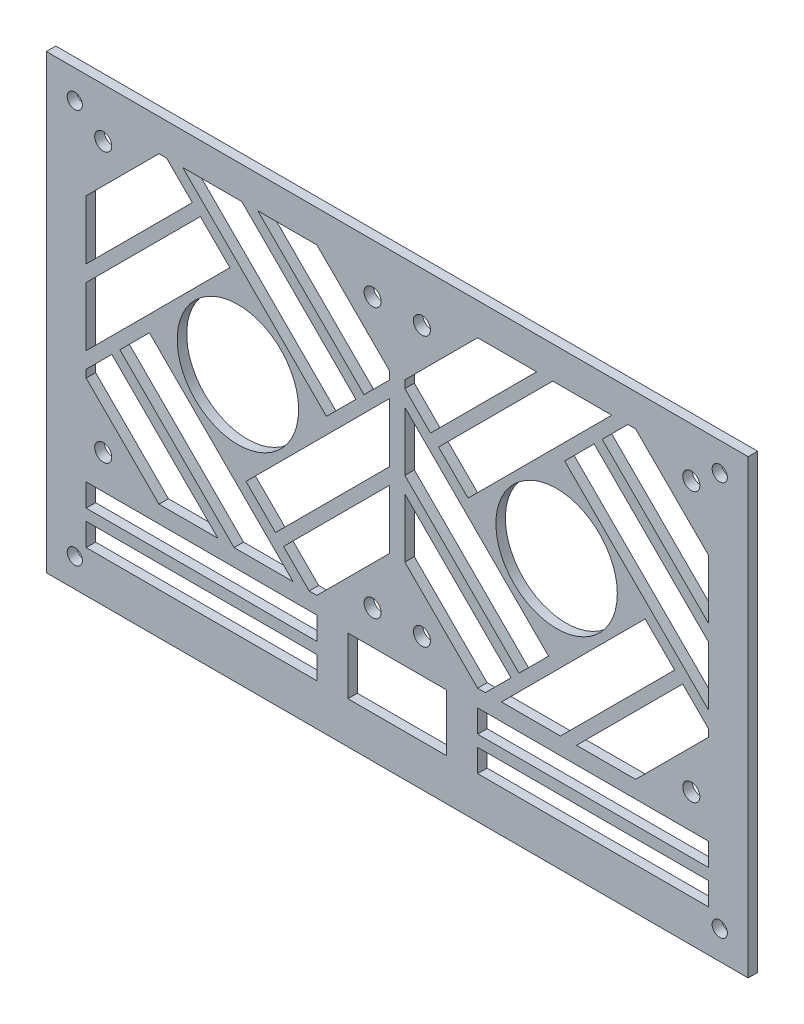
SolidWorks part; units mm, degrees
ref_plane "Front Plane" through (0, 0, 0) normal (0, 0, 1) x (1, 0, 0)
ref_plane "Top Plane" through (0, 0, 0) normal (0, 1, 0) x (1, 0, 0)
ref_plane "Right Plane" through (0, 0, 0) normal (1, 0, 0) x (0, 0, -1)
sketch "Sketch1" plane through (0, 0, 0) normal (0, 0, 1) x (1, 0, 0)
  line L1 (-92.5, -65.5) -> (92.5, -65.5)
  line L2 (-92.5, -65.5) -> (-92.5, 49.5)
  line L3 (-92.5, 49.5) -> (92.5, 49.5)
  line L4 (92.5, -65.5) -> (92.5, 49.5)
  point P0 (0, 0)
  dimension "D1" = 65.5
  dimension "D2" = 49.5
  dimension "D3" = 185
extrude "Boss-Extrude1" add sketch "Sketch1" along normal blind 2.5
sketch "Sketch2" plane through (0, 0, 2.5) normal (0, 0, 1) x (1, 0, 0)
  line L0 (-92.5, 49.5) -> (-92.5, -65.5) construction
  line L1 (92.5, -65.5) -> (92.5, 49.5) construction
  line L2 (-92.5, -65.5) -> (92.5, -65.5) construction
  circle A0 centre (-42, 5) radius 16
  circle A1 centre (42, 5) radius 16
  dimension "D1" = 50.5
  dimension "D2" = 32
  dimension "D3" = 32
  dimension "D4" = 50.5
  dimension "D5" = 70.5
  dimension "D6" = 70.5
extrude "Cut-Extrude1" cut sketch "Sketch2" against normal through all
sketch "Sketch5" plane through (0, 0, 2.5) normal (0, 0, 1) x (1, 0, 0)
  line L0 (-92.5, -65.5) -> (92.5, -65.5) construction
  line L1 (-13, -54.5) -> (13, -54.5)
  line L2 (-13, -54.5) -> (-13, -39.5)
  line L3 (-13, -39.5) -> (13, -39.5)
  line L4 (13, -54.5) -> (13, -39.5)
  line L5 (-13, -54.5) -> (13, -39.5) construction
  line L6 (-13, -39.5) -> (13, -54.5) construction
  point P0 (0, -47)
  dimension "D1" = 26
  dimension "D2" = 15
  dimension "D3" = 11
extrude "Cut-Extrude4" cut sketch "Sketch5" against normal blind 10
sketch "Sketch8" plane through (0, 0, 2.5) normal (0, 0, 1) x (1, 0, 0)
  line L0 (-82, 10.2548) -> (-54.0208, 38.234)
  line L1 (-82, 6.0122) -> (-51.8995, 36.1127)
  line L3 (-82, -9.5442) -> (-44.1213, 28.3345)
  line L5 (-82, 3.5923) -> (-46.2028, 30.416) construction
  line L6 (-82, -8.6433) -> (-48.2871, 32.5004) construction
  line L8 (-82, 25.8112) -> (-62.8112, 45)
  line L10 (-82, 10.2548) -> (-82, 25.8112)
  line L11 (0, -1000) -> (0, -37) construction
  line L13 (-21.1888, -35) -> (-2, -15.8112)
  line L21 (-43.0122, -35) -> (-73.1127, -4.8995)
  line L23 (-27.4558, -35) -> (-65.3345, 2.8787)
  line L24 (-73.1127, -4.8995) -> (-65.3345, 2.8787)
  line L25 (52.0715, -5.0757) -> (65.3345, 2.8787) construction
  line L26 (-43.0122, -35) -> (-27.4558, -35)
  line L27 (-82, -13.7868) -> (-75.234, -7.0208)
  line L29 (-47.2548, -35) -> (-75.234, -7.0208)
  line L30 (665.1295, -702.1295) -> (0, -37) construction
  line L31 (-18.6655, 7.1213) -> (-56.5442, 45)
  line L33 (-10.8873, 14.8995) -> (-40.9878, 45)
  line L34 (-10.8873, 14.8995) -> (-18.6655, 7.1213)
  line L35 (-2, 25.8112) -> (-21.1888, 45)
  line L37 (-8.766, 17.0208) -> (-36.7452, 45)
  line L38 (-2, 23.7868) -> (-8.766, 17.0208)
  line L39 (0, 47) -> (34606.2323, 34653.2323) construction
  line L40 (-62.8112, -35) -> (-47.2548, -35)
  line L41 (-82, -15.8112) -> (-82, -13.7868)
  line L42 (-62.8112, 45) -> (-60.7868, 45)
  line L43 (-2, -15.8112) -> (-2, -0.2548)
  line L44 (-72.3993, -25.4119) -> (-11.6007, 35.4119) construction
  line L45 (-54.7279, 17.7279) -> (-11.5944, -25.4056) construction
  line L46 (0, 47) -> (0, 50000) construction
  line L47 (-11.5944, -25.4056) -> (-54.7279, 17.7279) construction
  line L48 (56.5108, -9.5167) -> (73.1127, -4.8995) construction
  line L49 (72.3993, -25.4119) -> (11.6007, 35.4119) construction
  line L50 (-62.8112, -35) -> (-82, -15.8112)
  line L51 (11.5944, -25.4056) -> (54.7279, 17.7279) construction
  line L52 (-72.3993, -25.4119) -> (-11.6007, 35.4119) construction
  line L53 (-82, -9.5442) -> (-82, 6.0122)
  line L54 (-44.1213, 28.3345) -> (-51.8995, 36.1127)
  line L55 (-56.5442, 45) -> (-40.9878, 45)
  line L56 (-36.7452, 45) -> (-21.1888, 45)
  line L57 (-2, 23.7868) -> (-2, 25.8112)
  line L58 (-2, 3.9878) -> (-2, 19.5442)
  line L59 (-39.8787, -18.3345) -> (-32.1005, -26.1127)
  line L60 (-32.1005, -26.1127) -> (-2, 3.9878)
  line L61 (-54.0208, 38.234) -> (-60.7868, 45)
  line L62 (-29.9792, -28.234) -> (-2, -0.2548)
  line L63 (-23.2132, -35) -> (-21.1888, -35)
  line L64 (-29.9792, -28.234) -> (-23.2132, -35)
  line L65 (-39.8787, -18.3345) -> (-2, 19.5442)
  line L66 (-56.5108, -9.5167) -> (-73.1127, -4.8995) construction
  line L67 (-52.0715, -5.0757) -> (-65.3345, 2.8787) construction
  line L70 (54.7279, 17.7279) -> (11.5944, -25.4056) construction
  line L71 (72.3993, -25.4119) -> (11.6007, 35.4119) construction
  line L72 (82, -8.6433) -> (48.2871, 32.5004) construction
  line L73 (82, 3.5923) -> (46.2028, 30.416) construction
  line L74 (39.8787, -18.3345) -> (2, 19.5442)
  line L75 (29.9792, -28.234) -> (23.2132, -35)
  line L76 (23.2132, -35) -> (21.1888, -35)
  line L77 (29.9792, -28.234) -> (2, -0.2548)
  line L78 (54.0208, 38.234) -> (60.7868, 45)
  line L79 (32.1005, -26.1127) -> (2, 3.9878)
  line L80 (39.8787, -18.3345) -> (32.1005, -26.1127)
  line L81 (2, 3.9878) -> (2, 19.5442)
  line L82 (2, 23.7868) -> (2, 25.8112)
  line L83 (36.7452, 45) -> (21.1888, 45)
  line L84 (56.5442, 45) -> (40.9878, 45)
  line L85 (44.1213, 28.3345) -> (51.8995, 36.1127)
  line L86 (82, -9.5442) -> (82, 6.0122)
  line L87 (62.8112, -35) -> (82, -15.8112)
  line L88 (2, -15.8112) -> (2, -0.2548)
  line L89 (62.8112, 45) -> (60.7868, 45)
  line L90 (82, -15.8112) -> (82, -13.7868)
  line L91 (62.8112, -35) -> (47.2548, -35)
  line L92 (2, 23.7868) -> (8.766, 17.0208)
  line L93 (8.766, 17.0208) -> (36.7452, 45)
  line L94 (2, 25.8112) -> (21.1888, 45)
  line L95 (10.8873, 14.8995) -> (18.6655, 7.1213)
  line L96 (10.8873, 14.8995) -> (40.9878, 45)
  line L97 (18.6655, 7.1213) -> (56.5442, 45)
  line L98 (47.2548, -35) -> (75.234, -7.0208)
  line L99 (82, -13.7868) -> (75.234, -7.0208)
  line L100 (43.0122, -35) -> (27.4558, -35)
  line L101 (73.1127, -4.8995) -> (65.3345, 2.8787)
  line L102 (27.4558, -35) -> (65.3345, 2.8787)
  line L103 (43.0122, -35) -> (73.1127, -4.8995)
  line L106 (21.1888, -35) -> (2, -15.8112)
  line L107 (82, 10.2548) -> (82, 25.8112)
  line L108 (82, 25.8112) -> (62.8112, 45)
  line L109 (82, -9.5442) -> (44.1213, 28.3345)
  line L110 (82, 6.0122) -> (51.8995, 36.1127)
  line L111 (82, 10.2548) -> (54.0208, 38.234)
  line L113 (-75.234, -7.0208) -> (-46.0729, -51.7382) construction
  line L114 (-38.2948, -43.9601) -> (-83.0122, -14.799) construction
  circle A0 centre (-42, 5) radius 16 construction
  circle A1 centre (42, 5) radius 16 construction
  point P0 (-56.0271, 23.0544)
  point P21 (-60.6535, -29.3795)
  point P25 (-43.9911, -26.2429)
  point P114 (43.9911, -26.2429)
  point P115 (56.0271, 23.0544)
  dimension "D2" = 18
  dimension "D3" = 3
  dimension "D4" = 11
  dimension "D5" = 3
  dimension "D6" = 18
  dimension "D7" = 3
  dimension "D8" = 3
  dimension "D9" = 11
  dimension "D10" = 52.24
  dimension "D11" = 15
  dimension "D12" = 15
  dimension "D13" = 3
  dimension "D14" = 18
  dimension "D15" = 11
  dimension "D16" = 18
  dimension "D17" = 40
  dimension "D18" = 40
  dimension "D19" = 3
  dimension "D20" = 3
  dimension "D21" = 40
  dimension "D22" = 40
  dimension "D23" = 11
  dimension "D24" = 11
  dimension "D25" = 11
  dimension "D26" = 11
  dimension "D27" = 11
  dimension "D28" = 3
extrude "Cut-Extrude7" cut sketch "Sketch8" against normal blind 10
sketch "Sketch9" plane through (0, 0, 2.5) normal (0, 0, 1) x (1, 0, 0)
  line L0 (27.4558, -35) -> (43.0122, -35) construction
  line L1 (-82, -39.5) -> (-21.1888, -39.5)
  line L2 (-82, -39.5) -> (-82, -45.5)
  line L3 (-82, -45.5) -> (-21.1888, -45.5)
  line L4 (82, -39.5) -> (82, -45.5)
  line L5 (-82, -39.5) -> (-21.1888, -41.7248) construction
  line L6 (-82, -45.5) -> (-21.1888, -43.2752) construction
  line L7 (-82, 6.0122) -> (-82, -9.5442) construction
  line L8 (82, -9.5442) -> (82, 6.0122) construction
  line L9 (-82, -48.5) -> (-21.1888, -48.5)
  line L10 (-82, -54.5) -> (-21.1888, -54.5)
  line L11 (-82, -48.5) -> (-82, -54.5)
  line L12 (82, -48.5) -> (82, -54.5)
  line L15 (-21.1888, -54.5) -> (-21.1888, -48.5)
  line L17 (21.1888, -54.5) -> (21.1888, -48.5)
  line L18 (21.1888, -1035) -> (21.1888, 48965) construction
  line L19 (-21.1888, -1035) -> (-21.1888, 48965) construction
  line L20 (21.1888, -39.5) -> (82, -39.5)
  line L21 (21.1888, -41.7248) -> (82, -39.5) construction
  line L22 (21.1888, -43.2752) -> (82, -45.5) construction
  line L25 (21.1888, -45.5) -> (82, -45.5)
  line L27 (21.1888, -54.5) -> (82, -54.5)
  line L28 (0.2654, -40.5081) -> (0.2664, -40.4919) construction
  line L30 (-21.1888, -45.5) -> (-21.1888, -39.5)
  line L31 (21.1888, -45.5) -> (21.1888, -39.5)
  line L32 (21.1888, -48.5) -> (82, -48.5)
  point P0 (0, -42.5)
  point P15 (0, -44.6614)
  dimension "D1" = 6
  dimension "D2" = 4.5
  dimension "D3" = 6
  dimension "D4" = 3
  dimension "D5" = 6
extrude "Cut-Extrude8" cut sketch "Sketch9" against normal blind 10
sketch "Sketch10" plane through (0, 0, 2.5) normal (0, 0, 1) x (1, 0, 0)
  line L0 (0, 0) -> (0, 50000) construction
  circle A0 centre (-77.5, 40.5) radius 2.25
  circle A1 centre (-42, 5) radius 16 construction
  circle A2 centre (-6.5, 40.5) radius 2.25
  circle A3 centre (-6.5, -30.5) radius 2.25
  circle A4 centre (-77.5, -30.5) radius 2.25
  circle A5 centre (77.5, -30.5) radius 2.25
  circle A6 centre (6.5, -30.5) radius 2.25
  circle A7 centre (6.5, 40.5) radius 2.25
  circle A8 centre (77.5, 40.5) radius 2.25
  dimension "D1" = 4.5
  dimension "D2" = 35.5
  dimension "D3" = 35.5
  dimension "D4" = 2
  dimension "D5" = 2
extrude "Cut-Extrude9" cut sketch "Sketch10" against normal through all both and the other way through all
sketch "Sketch11" plane through (0, 0, 2.5) normal (0, 0, 1) x (1, 0, 0)
  line L0 (92.5, 49.5) -> (-92.5, 49.5) construction
  line L1 (-92.5, 49.5) -> (-92.5, -65.5) construction
  line L2 (-92.5, -65.5) -> (92.5, -65.5) construction
  line L3 (92.5, -65.5) -> (92.5, 49.5) construction
  circle A0 centre (-85, 46) radius 2
  circle A1 centre (85, 46) radius 2
  circle A2 centre (85, -58) radius 2
  circle A3 centre (-85, -58) radius 2
  dimension "D1" = 3.5
  dimension "D2" = 7.5
  dimension "D3" = 4
  dimension "D6" = 7.5
  dimension "D7" = 7.5
  dimension "D4" = 2
  dimension "D5" = 2
extrude "Cut-Extrude11" cut sketch "Sketch11" against normal through all
sketch "Sketch12" plane through (0, 0, 2.5) normal (0, 0, 1) x (1, 0, 0)
  line L0 (92.5, -65.5) -> (92.5, 49.5) construction
  line L1 (-92.5, 49.5) -> (92.5, 49.5)
  line L2 (-92.5, 49.5) -> (-92.5, 53.5)
  line L3 (-92.5, 53.5) -> (92.5, 53.5)
  line L4 (92.5, 49.5) -> (92.5, 53.5)
  dimension "D1" = 4
extrude "Boss-Extrude2" add sketch "Sketch12" against normal blind 2.5
